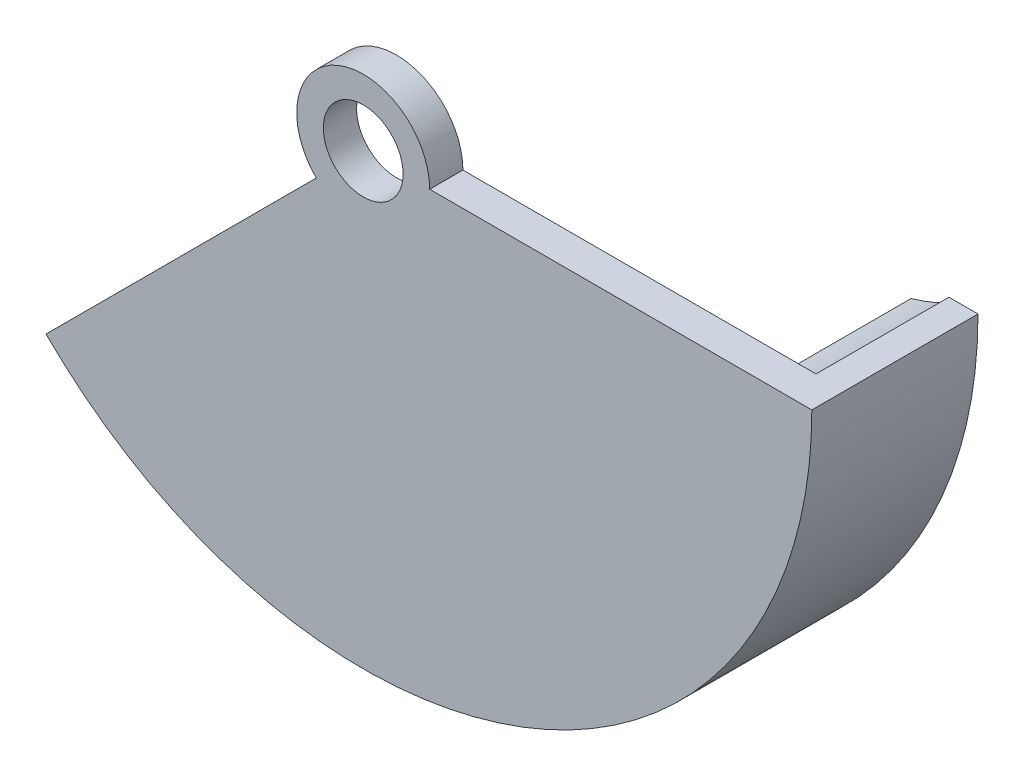
SolidWorks part; units mm, degrees
ref_plane "Front Plane" through (0, 0, 0) normal (0, 0, 1) x (1, 0, 0)
ref_plane "Top Plane" through (0, 0, 0) normal (0, 1, 0) x (1, 0, 0)
ref_plane "Right Plane" through (0, 0, 0) normal (1, 0, 0) x (0, 0, -1)
sketch "Sketch4" plane through (0, 0, 0) normal (0, 0, 1) x (1, 0, 0)
  arc A0 (11.9321, 56.2483) -> (10.5015, 56.5329) centre (0, 0) ccw construction
  arc A1 (10.5015, 56.5329) -> (8.9782, 62.4843) centre (-19.1705, 52.1088) ccw construction
  arc A2 (8.9782, 62.4843) -> (7.4999, 62.6789) centre (0, 0) ccw construction
  arc A3 (7.4999, 62.6789) -> (4.4881, 57.3246) centre (32.004, 45.3715) ccw construction
  arc A4 (11.9321, 56.2483) -> (10.5015, 56.5329) centre (0, 0) ccw
  arc A5 (10.5015, 56.5329) -> (8.9782, 62.4843) centre (-19.1705, 52.1088) ccw
  arc A6 (8.9782, 62.4843) -> (7.4999, 62.6789) centre (0, 0) ccw
  arc A7 (7.4999, 62.6789) -> (4.4881, 57.3246) centre (32.004, 45.3715) ccw
  arc A8 (15.6169, 61.1637) -> (11.9321, 56.2483) centre (37.6524, 40.806) ccw
  arc A9 (17.0572, 60.7778) -> (15.6169, 61.1637) centre (0, 0) ccw
  arc A10 (17.7907, 54.6785) -> (17.0572, 60.7778) centre (-12.2049, 54.1652) ccw
  arc A11 (19.1719, 54.2097) -> (17.7907, 54.6785) centre (0, 0) ccw
  arc A12 (23.4668, 58.6021) -> (19.1719, 54.2097) centre (42.6565, 35.5423) ccw
  arc A13 (24.8444, 58.0314) -> (23.4668, 58.6021) centre (0, 0) ccw
  arc A14 (24.7754, 51.8886) -> (24.8444, 58.0314) centre (-5.0305, 55.2949) ccw
  arc A15 (26.0837, 51.2435) -> (24.7754, 51.8886) centre (0, 0) ccw
  arc A16 (30.9151, 55.0377) -> (26.0837, 51.2435) centre (46.9308, 29.6704) ccw
  arc A17 (32.2065, 54.2921) -> (30.9151, 55.0377) centre (0, 0) ccw
  arc A18 (31.3363, 48.2108) -> (32.2065, 54.2921) centre (2.2299, 55.4785) ccw
  arc A19 (32.5491, 47.4005) -> (31.3363, 48.2108) centre (0, 0) ccw
  arc A20 (37.8345, 50.5316) -> (32.5491, 47.4005) centre (50.4021, 23.2909) ccw
  arc A21 (39.0175, 49.6239) -> (37.8345, 50.5316) centre (0, 0) ccw
  arc A22 (37.361, 43.7082) -> (39.0175, 49.6239) centre (9.4522, 54.7128) ccw
  arc A23 (38.4577, 42.7464) -> (37.361, 43.7082) centre (0, 0) ccw
  arc A24 (44.1065, 45.1609) -> (38.4577, 42.7464) centre (53.0109, 16.5128) ccw
  arc A25 (45.1609, 44.1065) -> (44.1065, 45.1609) centre (0, 0) ccw
  arc A26 (42.7464, 38.4577) -> (45.1609, 44.1065) centre (16.5128, 53.0109) ccw
  arc A27 (43.7082, 37.361) -> (42.7464, 38.4577) centre (0, 0) ccw
  arc A28 (49.6239, 39.0175) -> (43.7082, 37.361) centre (54.7128, 9.4522) ccw
  arc A29 (50.5316, 37.8345) -> (49.6239, 39.0175) centre (0, 0) ccw
  arc A30 (47.4005, 32.5491) -> (50.5316, 37.8345) centre (23.2909, 50.4021) ccw
  arc A31 (48.2108, 31.3363) -> (47.4005, 32.5491) centre (0, 0) ccw
  arc A32 (54.2921, 32.2065) -> (48.2108, 31.3363) centre (55.4785, 2.2299) ccw
  arc A33 (55.0377, 30.9151) -> (54.2921, 32.2065) centre (0, 0) ccw
  arc A34 (51.2435, 26.0837) -> (55.0377, 30.9151) centre (29.6704, 46.9308) ccw
  arc A35 (51.8886, 24.7754) -> (51.2435, 26.0837) centre (0, 0) ccw
  arc A36 (58.0314, 24.8444) -> (51.8886, 24.7754) centre (55.2949, -5.0305) ccw
  arc A37 (58.6021, 23.4668) -> (58.0314, 24.8444) centre (0, 0) ccw
  arc A38 (54.2097, 19.1719) -> (58.6021, 23.4668) centre (35.5423, 42.6565) ccw
  arc A39 (54.6785, 17.7907) -> (54.2097, 19.1719) centre (0, 0) ccw
  arc A40 (60.7778, 17.0572) -> (54.6785, 17.7907) centre (54.1652, -12.2049) ccw
  arc A41 (61.1637, 15.6169) -> (60.7778, 17.0572) centre (0, 0) ccw
  arc A42 (56.2483, 11.9321) -> (61.1637, 15.6169) centre (40.806, 37.6524) ccw
  arc A43 (56.5329, 10.5015) -> (56.2483, 11.9321) centre (0, 0) ccw
  arc A44 (62.4843, 8.9782) -> (56.5329, 10.5015) centre (52.1088, -19.1705) ccw
  arc A45 (62.6789, 7.4999) -> (62.4843, 8.9782) centre (0, 0) ccw
  arc A46 (57.3246, 4.4881) -> (62.6789, 7.4999) centre (45.3715, 32.004) ccw
  arc A47 (57.42, 3.0326) -> (57.3246, 4.4881) centre (0, 0) ccw
  arc A48 (63.1216, 0.7455) -> (57.42, 3.0326) centre (49.1607, -25.8081) ccw
  arc A49 (63.1216, -0.7455) -> (63.1216, 0.7455) centre (0, 0) ccw
  arc A50 (57.42, -3.0326) -> (63.1216, -0.7455) centre (49.1607, 25.8081) ccw
  arc A51 (57.3246, -4.4881) -> (57.42, -3.0326) centre (0, 0) ccw
  arc A52 (62.6789, -7.4999) -> (57.3246, -4.4881) centre (45.3715, -32.004) ccw
  arc A53 (62.4843, -8.9782) -> (62.6789, -7.4999) centre (0, 0) ccw
  arc A54 (56.5329, -10.5015) -> (62.4843, -8.9782) centre (52.1088, 19.1705) ccw
  arc A55 (56.2483, -11.9321) -> (56.5329, -10.5015) centre (0, 0) ccw
  arc A56 (61.1637, -15.6169) -> (56.2483, -11.9321) centre (40.806, -37.6524) ccw
  arc A57 (60.7778, -17.0572) -> (61.1637, -15.6169) centre (0, 0) ccw
  arc A58 (54.6785, -17.7907) -> (60.7778, -17.0572) centre (54.1652, 12.2049) ccw
  arc A59 (54.2097, -19.1719) -> (54.6785, -17.7907) centre (0, 0) ccw
  arc A60 (58.6021, -23.4668) -> (54.2097, -19.1719) centre (35.5423, -42.6565) ccw
  arc A61 (58.0314, -24.8444) -> (58.6021, -23.4668) centre (0, 0) ccw
  arc A62 (51.8886, -24.7754) -> (58.0314, -24.8444) centre (55.2949, 5.0305) ccw
  arc A63 (51.2435, -26.0837) -> (51.8886, -24.7754) centre (0, 0) ccw
  arc A64 (55.0377, -30.9151) -> (51.2435, -26.0837) centre (29.6704, -46.9308) ccw
  arc A65 (54.2921, -32.2065) -> (55.0377, -30.9151) centre (0, 0) ccw
  arc A66 (48.2108, -31.3363) -> (54.2921, -32.2065) centre (55.4785, -2.2299) ccw
  arc A67 (47.4005, -32.5491) -> (48.2108, -31.3363) centre (0, 0) ccw
  arc A68 (50.5316, -37.8345) -> (47.4005, -32.5491) centre (23.2909, -50.4021) ccw
  arc A69 (49.6239, -39.0175) -> (50.5316, -37.8345) centre (0, 0) ccw
  arc A70 (43.7082, -37.361) -> (49.6239, -39.0175) centre (54.7128, -9.4522) ccw
  arc A71 (42.7464, -38.4577) -> (43.7082, -37.361) centre (0, 0) ccw
  arc A72 (45.1609, -44.1065) -> (42.7464, -38.4577) centre (16.5128, -53.0109) ccw
  arc A73 (44.1065, -45.1609) -> (45.1609, -44.1065) centre (0, 0) ccw
  arc A74 (38.4577, -42.7464) -> (44.1065, -45.1609) centre (53.0109, -16.5128) ccw
  arc A75 (37.361, -43.7082) -> (38.4577, -42.7464) centre (0, 0) ccw
  arc A76 (39.0175, -49.6239) -> (37.361, -43.7082) centre (9.4522, -54.7128) ccw
  arc A77 (37.8345, -50.5316) -> (39.0175, -49.6239) centre (0, 0) ccw
  arc A78 (32.5491, -47.4005) -> (37.8345, -50.5316) centre (50.4021, -23.2909) ccw
  arc A79 (31.3363, -48.2108) -> (32.5491, -47.4005) centre (0, 0) ccw
  arc A80 (32.2065, -54.2921) -> (31.3363, -48.2108) centre (2.2299, -55.4785) ccw
  arc A81 (30.9151, -55.0377) -> (32.2065, -54.2921) centre (0, 0) ccw
  arc A82 (26.0837, -51.2435) -> (30.9151, -55.0377) centre (46.9308, -29.6704) ccw
  arc A83 (24.7754, -51.8886) -> (26.0837, -51.2435) centre (0, 0) ccw
  arc A84 (24.8444, -58.0314) -> (24.7754, -51.8886) centre (-5.0305, -55.2949) ccw
  arc A85 (23.4668, -58.6021) -> (24.8444, -58.0314) centre (0, 0) ccw
  arc A86 (19.1719, -54.2097) -> (23.4668, -58.6021) centre (42.6565, -35.5423) ccw
  arc A87 (17.7907, -54.6785) -> (19.1719, -54.2097) centre (0, 0) ccw
  arc A88 (17.0572, -60.7778) -> (17.7907, -54.6785) centre (-12.2049, -54.1652) ccw
  arc A89 (15.6169, -61.1637) -> (17.0572, -60.7778) centre (0, 0) ccw
  arc A90 (11.9321, -56.2483) -> (15.6169, -61.1637) centre (37.6524, -40.806) ccw
  arc A91 (10.5015, -56.5329) -> (11.9321, -56.2483) centre (0, 0) ccw
  arc A92 (8.9782, -62.4843) -> (10.5015, -56.5329) centre (-19.1705, -52.1088) ccw
  arc A93 (7.4999, -62.6789) -> (8.9782, -62.4843) centre (0, 0) ccw
  arc A94 (4.4881, -57.3246) -> (7.4999, -62.6789) centre (32.004, -45.3715) ccw
  arc A95 (3.0326, -57.42) -> (4.4881, -57.3246) centre (0, 0) ccw
  arc A96 (0.7455, -63.1216) -> (3.0326, -57.42) centre (-25.8081, -49.1607) ccw
  arc A97 (-0.7455, -63.1216) -> (0.7455, -63.1216) centre (0, 0) ccw
  arc A98 (-3.0326, -57.42) -> (-0.7455, -63.1216) centre (25.8081, -49.1607) ccw
  arc A99 (-4.4881, -57.3246) -> (-3.0326, -57.42) centre (0, 0) ccw
  arc A100 (-7.4999, -62.6789) -> (-4.4881, -57.3246) centre (-32.004, -45.3715) ccw
  arc A101 (-8.9782, -62.4843) -> (-7.4999, -62.6789) centre (0, 0) ccw
  arc A102 (-10.5015, -56.5329) -> (-8.9782, -62.4843) centre (19.1705, -52.1088) ccw
  arc A103 (-11.9321, -56.2483) -> (-10.5015, -56.5329) centre (0, 0) ccw
  arc A104 (-15.6169, -61.1637) -> (-11.9321, -56.2483) centre (-37.6524, -40.806) ccw
  arc A105 (-17.0572, -60.7778) -> (-15.6169, -61.1637) centre (0, 0) ccw
  arc A106 (-17.7907, -54.6785) -> (-17.0572, -60.7778) centre (12.2049, -54.1652) ccw
  arc A107 (-19.1719, -54.2097) -> (-17.7907, -54.6785) centre (0, 0) ccw
  arc A108 (-23.4668, -58.6021) -> (-19.1719, -54.2097) centre (-42.6565, -35.5423) ccw
  arc A109 (-24.8444, -58.0314) -> (-23.4668, -58.6021) centre (0, 0) ccw
  arc A110 (-24.7754, -51.8886) -> (-24.8444, -58.0314) centre (5.0305, -55.2949) ccw
  arc A111 (-26.0837, -51.2435) -> (-24.7754, -51.8886) centre (0, 0) ccw
  arc A112 (-30.9151, -55.0377) -> (-26.0837, -51.2435) centre (-46.9308, -29.6704) ccw
  arc A113 (-32.2065, -54.2921) -> (-30.9151, -55.0377) centre (0, 0) ccw
  arc A114 (-31.3363, -48.2108) -> (-32.2065, -54.2921) centre (-2.2299, -55.4785) ccw
  arc A115 (-32.5491, -47.4005) -> (-31.3363, -48.2108) centre (0, 0) ccw
  arc A116 (-37.8345, -50.5316) -> (-32.5491, -47.4005) centre (-50.4021, -23.2909) ccw
  arc A117 (-39.0175, -49.6239) -> (-37.8345, -50.5316) centre (0, 0) ccw
  arc A118 (-37.361, -43.7082) -> (-39.0175, -49.6239) centre (-9.4522, -54.7128) ccw
  arc A119 (-38.4577, -42.7464) -> (-37.361, -43.7082) centre (0, 0) ccw
  arc A120 (-44.1065, -45.1609) -> (-38.4577, -42.7464) centre (-53.0109, -16.5128) ccw
  arc A121 (-45.1609, -44.1065) -> (-44.1065, -45.1609) centre (0, 0) ccw
  arc A122 (-42.7464, -38.4577) -> (-45.1609, -44.1065) centre (-16.5128, -53.0109) ccw
  arc A123 (-43.7082, -37.361) -> (-42.7464, -38.4577) centre (0, 0) ccw
  arc A124 (-49.6239, -39.0175) -> (-43.7082, -37.361) centre (-54.7128, -9.4522) ccw
  arc A125 (-50.5316, -37.8345) -> (-49.6239, -39.0175) centre (0, 0) ccw
  arc A126 (-47.4005, -32.5491) -> (-50.5316, -37.8345) centre (-23.2909, -50.4021) ccw
  arc A127 (-48.2108, -31.3363) -> (-47.4005, -32.5491) centre (0, 0) ccw
  arc A128 (-54.2921, -32.2065) -> (-48.2108, -31.3363) centre (-55.4785, -2.2299) ccw
  arc A129 (-55.0377, -30.9151) -> (-54.2921, -32.2065) centre (0, 0) ccw
  arc A130 (-51.2435, -26.0837) -> (-55.0377, -30.9151) centre (-29.6704, -46.9308) ccw
  arc A131 (-51.8886, -24.7754) -> (-51.2435, -26.0837) centre (0, 0) ccw
  arc A132 (-58.0314, -24.8444) -> (-51.8886, -24.7754) centre (-55.2949, 5.0305) ccw
  arc A133 (-58.6021, -23.4668) -> (-58.0314, -24.8444) centre (0, 0) ccw
  arc A134 (-54.2097, -19.1719) -> (-58.6021, -23.4668) centre (-35.5423, -42.6565) ccw
  arc A135 (-54.6785, -17.7907) -> (-54.2097, -19.1719) centre (0, 0) ccw
  arc A136 (-60.7778, -17.0572) -> (-54.6785, -17.7907) centre (-54.1652, 12.2049) ccw
  arc A137 (-61.1637, -15.6169) -> (-60.7778, -17.0572) centre (0, 0) ccw
  arc A138 (-56.2483, -11.9321) -> (-61.1637, -15.6169) centre (-40.806, -37.6524) ccw
  arc A139 (-56.5329, -10.5015) -> (-56.2483, -11.9321) centre (0, 0) ccw
  arc A140 (-62.4843, -8.9782) -> (-56.5329, -10.5015) centre (-52.1088, 19.1705) ccw
  arc A141 (-62.6789, -7.4999) -> (-62.4843, -8.9782) centre (0, 0) ccw
  arc A142 (-57.3246, -4.4881) -> (-62.6789, -7.4999) centre (-45.3715, -32.004) ccw
  arc A143 (-57.42, -3.0326) -> (-57.3246, -4.4881) centre (0, 0) ccw
  arc A144 (-63.1216, -0.7455) -> (-57.42, -3.0326) centre (-49.1607, 25.8081) ccw
  arc A145 (-63.1216, 0.7455) -> (-63.1216, -0.7455) centre (0, 0) ccw
  arc A146 (-57.42, 3.0326) -> (-63.1216, 0.7455) centre (-49.1607, -25.8081) ccw
  arc A147 (-57.3246, 4.4881) -> (-57.42, 3.0326) centre (0, 0) ccw
  arc A148 (-62.6789, 7.4999) -> (-57.3246, 4.4881) centre (-45.3715, 32.004) ccw
  arc A149 (-62.4843, 8.9782) -> (-62.6789, 7.4999) centre (0, 0) ccw
  arc A150 (-56.5329, 10.5015) -> (-62.4843, 8.9782) centre (-52.1088, -19.1705) ccw
  arc A151 (-56.2483, 11.9321) -> (-56.5329, 10.5015) centre (0, 0) ccw
  arc A152 (-61.1637, 15.6169) -> (-56.2483, 11.9321) centre (-40.806, 37.6524) ccw
  arc A153 (-60.7778, 17.0572) -> (-61.1637, 15.6169) centre (0, 0) ccw
  arc A154 (-54.6785, 17.7907) -> (-60.7778, 17.0572) centre (-54.1652, -12.2049) ccw
  arc A155 (-54.2097, 19.1719) -> (-54.6785, 17.7907) centre (0, 0) ccw
  arc A156 (-58.6021, 23.4668) -> (-54.2097, 19.1719) centre (-35.5423, 42.6565) ccw
  arc A157 (-58.0314, 24.8444) -> (-58.6021, 23.4668) centre (0, 0) ccw
  arc A158 (-51.8886, 24.7754) -> (-58.0314, 24.8444) centre (-55.2949, -5.0305) ccw
  arc A159 (-51.2435, 26.0837) -> (-51.8886, 24.7754) centre (0, 0) ccw
  arc A160 (-55.0377, 30.9151) -> (-51.2435, 26.0837) centre (-29.6704, 46.9308) ccw
  arc A161 (-54.2921, 32.2065) -> (-55.0377, 30.9151) centre (0, 0) ccw
  arc A162 (-48.2108, 31.3363) -> (-54.2921, 32.2065) centre (-55.4785, 2.2299) ccw
  arc A163 (-47.4005, 32.5491) -> (-48.2108, 31.3363) centre (0, 0) ccw
  arc A164 (-50.5316, 37.8345) -> (-47.4005, 32.5491) centre (-23.2909, 50.4021) ccw
  arc A165 (-49.6239, 39.0175) -> (-50.5316, 37.8345) centre (0, 0) ccw
  arc A166 (-43.7082, 37.361) -> (-49.6239, 39.0175) centre (-54.7128, 9.4522) ccw
  arc A167 (-42.7464, 38.4577) -> (-43.7082, 37.361) centre (0, 0) ccw
  arc A168 (-45.1609, 44.1065) -> (-42.7464, 38.4577) centre (-16.5128, 53.0109) ccw
  arc A169 (-44.1065, 45.1609) -> (-45.1609, 44.1065) centre (0, 0) ccw
  arc A170 (-38.4577, 42.7464) -> (-44.1065, 45.1609) centre (-53.0109, 16.5128) ccw
  arc A171 (-37.361, 43.7082) -> (-38.4577, 42.7464) centre (0, 0) ccw
  arc A172 (-39.0175, 49.6239) -> (-37.361, 43.7082) centre (-9.4522, 54.7128) ccw
  arc A173 (-37.8345, 50.5316) -> (-39.0175, 49.6239) centre (0, 0) ccw
  arc A174 (-32.5491, 47.4005) -> (-37.8345, 50.5316) centre (-50.4021, 23.2909) ccw
  arc A175 (-31.3363, 48.2108) -> (-32.5491, 47.4005) centre (0, 0) ccw
  arc A176 (-32.2065, 54.2921) -> (-31.3363, 48.2108) centre (-2.2299, 55.4785) ccw
  arc A177 (-30.9151, 55.0377) -> (-32.2065, 54.2921) centre (0, 0) ccw
  arc A178 (-26.0837, 51.2435) -> (-30.9151, 55.0377) centre (-46.9308, 29.6704) ccw
  arc A179 (-24.7754, 51.8886) -> (-26.0837, 51.2435) centre (0, 0) ccw
  arc A180 (-24.8444, 58.0314) -> (-24.7754, 51.8886) centre (5.0305, 55.2949) ccw
  arc A181 (-23.4668, 58.6021) -> (-24.8444, 58.0314) centre (0, 0) ccw
  arc A182 (-19.1719, 54.2097) -> (-23.4668, 58.6021) centre (-42.6565, 35.5423) ccw
  arc A183 (-17.7907, 54.6785) -> (-19.1719, 54.2097) centre (0, 0) ccw
  arc A184 (-17.0572, 60.7778) -> (-17.7907, 54.6785) centre (12.2049, 54.1652) ccw
  arc A185 (-15.6169, 61.1637) -> (-17.0572, 60.7778) centre (0, 0) ccw
  arc A186 (-11.9321, 56.2483) -> (-15.6169, 61.1637) centre (-37.6524, 40.806) ccw
  arc A187 (-10.5015, 56.5329) -> (-11.9321, 56.2483) centre (0, 0) ccw
  arc A188 (-8.9782, 62.4843) -> (-10.5015, 56.5329) centre (19.1705, 52.1088) ccw
  arc A189 (-7.4999, 62.6789) -> (-8.9782, 62.4843) centre (0, 0) ccw
  arc A190 (-4.4881, 57.3246) -> (-7.4999, 62.6789) centre (-32.004, 45.3715) ccw
  arc A191 (-3.0326, 57.42) -> (-4.4881, 57.3246) centre (0, 0) ccw
  arc A192 (-0.7455, 63.1216) -> (-3.0326, 57.42) centre (25.8081, 49.1607) ccw
  arc A193 (0.7455, 63.1216) -> (-0.7455, 63.1216) centre (0, 0) ccw
  arc A194 (3.0326, 57.42) -> (0.7455, 63.1216) centre (-25.8081, 49.1607) ccw
  arc A195 (4.4881, 57.3246) -> (3.0326, 57.42) centre (0, 0) ccw
  circle A196 centre (0, 0) radius 67.5
  dimension "D1" = 48
extrude "Boss-Extrude1" add sketch "Sketch4" along normal blind 50
sketch "Sketch5" plane through (0, 0, 0) normal (0, 0, -1) x (-1, 0, 0)
  line L0 (0, 0) -> (-67.5, 0)
  line L1 (0, 0) -> (47.7297, -47.7297)
  circle A0 centre (0, 0) radius 67.5 construction
  arc A1 (47.7297, -47.7297) -> (-67.5, 0) centre (0, 0) ccw
extrude "Cut-Extrude2" cut sketch "Sketch5" against normal blind 250 contours L1 A1 L0
sketch "Sketch6" plane through (0, 0, 50) normal (0, 0, 1) x (1, 0, 0)
  line L0 (0, 0) -> (67.5, 0)
  line L1 (0, 0) -> (-47.7297, -47.7297)
  arc A0 (67.5, 0) -> (-47.7297, -47.7297) centre (0, 0) cw
  arc A1 (-47.7297, -47.7297) -> (67.5, 0) centre (0, 0) ccw construction
extrude "Boss-Extrude2" add sketch "Sketch6" along normal blind 5 contours A0 L0 L1
sketch "Sketch7" plane through (0, 0, 55) normal (0, 0, 1) x (1, 0, 0)
  circle A0 centre (0, 0) radius 6
extrude "Cut-Extrude3" cut sketch "Sketch7" against normal blind 5
sketch "Sketch8" plane through (0, 0, 55) normal (0, 0, 1) x (1, 0, 0)
  circle A0 centre (0, 0) radius 6
  circle A1 centre (0, 0) radius 10
extrude "Boss-Extrude3" add sketch "Sketch8" against normal blind 5
sketch "Sketch9" plane through (0, 0, 0) normal (0, 0, -1) x (-1, 0, 0)
  line L2 (47.7297, -47.7297) -> (44.6368, -44.6368)
  line L3 (-63.126, 0) -> (-67.5, 0)
  line L4 (47.7297, -47.7297) -> (44.6368, -44.6368)
  line L5 (-63.126, 0) -> (-67.5, 0)
  arc A74 (-67.5, 0) -> (47.7297, -47.7297) centre (0, 0) ccw
  arc A75 (44.1065, -45.1609) -> (44.6368, -44.6368) centre (0, 0) ccw
  arc A76 (38.4577, -42.7464) -> (44.1065, -45.1609) centre (53.0109, -16.5128) ccw
  arc A77 (37.361, -43.7082) -> (38.4577, -42.7464) centre (0, 0) ccw
  arc A78 (39.0175, -49.6239) -> (37.361, -43.7082) centre (9.4522, -54.7128) ccw
  arc A79 (37.8345, -50.5316) -> (39.0175, -49.6239) centre (0, 0) ccw
  arc A80 (32.5491, -47.4005) -> (37.8345, -50.5316) centre (50.4021, -23.2909) ccw
  arc A81 (31.3363, -48.2108) -> (32.5491, -47.4005) centre (0, 0) ccw
  arc A82 (32.2065, -54.2921) -> (31.3363, -48.2108) centre (2.2299, -55.4785) ccw
  arc A83 (30.9151, -55.0377) -> (32.2065, -54.2921) centre (0, 0) ccw
  arc A84 (26.0837, -51.2435) -> (30.9151, -55.0377) centre (46.9308, -29.6704) ccw
  arc A85 (24.7754, -51.8886) -> (26.0837, -51.2435) centre (0, 0) ccw
  arc A86 (24.8444, -58.0314) -> (24.7754, -51.8886) centre (-5.0305, -55.2949) ccw
  arc A87 (23.4668, -58.6021) -> (24.8444, -58.0314) centre (0, 0) ccw
  arc A88 (19.1719, -54.2097) -> (23.4668, -58.6021) centre (42.6565, -35.5423) ccw
  arc A89 (17.7907, -54.6785) -> (19.1719, -54.2097) centre (0, 0) ccw
  arc A90 (17.0572, -60.7778) -> (17.7907, -54.6785) centre (-12.2049, -54.1652) ccw
  arc A91 (15.6169, -61.1637) -> (17.0572, -60.7778) centre (0, 0) ccw
  arc A92 (11.9321, -56.2483) -> (15.6169, -61.1637) centre (37.6524, -40.806) ccw
  arc A93 (10.5015, -56.5329) -> (11.9321, -56.2483) centre (0, 0) ccw
  arc A94 (8.9782, -62.4843) -> (10.5015, -56.5329) centre (-19.1705, -52.1088) ccw
  arc A95 (7.4999, -62.6789) -> (8.9782, -62.4843) centre (0, 0) ccw
  arc A96 (4.4881, -57.3246) -> (7.4999, -62.6789) centre (32.004, -45.3715) ccw
  arc A97 (3.0326, -57.42) -> (4.4881, -57.3246) centre (0, 0) ccw
  arc A98 (0.7455, -63.1216) -> (3.0326, -57.42) centre (-25.8081, -49.1607) ccw
  arc A99 (-0.7455, -63.1216) -> (0.7455, -63.1216) centre (0, 0) ccw
  arc A100 (-3.0326, -57.42) -> (-0.7455, -63.1216) centre (25.8081, -49.1607) ccw
  arc A101 (-4.4881, -57.3246) -> (-3.0326, -57.42) centre (0, 0) ccw
  arc A102 (-7.4999, -62.6789) -> (-4.4881, -57.3246) centre (-32.004, -45.3715) ccw
  arc A103 (-8.9782, -62.4843) -> (-7.4999, -62.6789) centre (0, 0) ccw
  arc A104 (-10.5015, -56.5329) -> (-8.9782, -62.4843) centre (19.1705, -52.1088) ccw
  arc A105 (-11.9321, -56.2483) -> (-10.5015, -56.5329) centre (0, 0) ccw
  arc A106 (-15.6169, -61.1637) -> (-11.9321, -56.2483) centre (-37.6524, -40.806) ccw
  arc A107 (-17.0572, -60.7778) -> (-15.6169, -61.1637) centre (0, 0) ccw
  arc A108 (-17.7907, -54.6785) -> (-17.0572, -60.7778) centre (12.2049, -54.1652) ccw
  arc A109 (-19.1719, -54.2097) -> (-17.7907, -54.6785) centre (0, 0) ccw
  arc A110 (-23.4668, -58.6021) -> (-19.1719, -54.2097) centre (-42.6565, -35.5423) ccw
  arc A111 (-24.8444, -58.0314) -> (-23.4668, -58.6021) centre (0, 0) ccw
  arc A112 (-24.7754, -51.8886) -> (-24.8444, -58.0314) centre (5.0305, -55.2949) ccw
  arc A113 (-26.0837, -51.2435) -> (-24.7754, -51.8886) centre (0, 0) ccw
  arc A114 (-30.9151, -55.0377) -> (-26.0837, -51.2435) centre (-46.9308, -29.6704) ccw
  arc A115 (-32.2065, -54.2921) -> (-30.9151, -55.0377) centre (0, 0) ccw
  arc A116 (-31.3363, -48.2108) -> (-32.2065, -54.2921) centre (-2.2299, -55.4785) ccw
  arc A117 (-32.5491, -47.4005) -> (-31.3363, -48.2108) centre (0, 0) ccw
  arc A118 (-37.8345, -50.5316) -> (-32.5491, -47.4005) centre (-50.4021, -23.2909) ccw
  arc A119 (-39.0175, -49.6239) -> (-37.8345, -50.5316) centre (0, 0) ccw
  arc A120 (-37.361, -43.7082) -> (-39.0175, -49.6239) centre (-9.4522, -54.7128) ccw
  arc A121 (-38.4577, -42.7464) -> (-37.361, -43.7082) centre (0, 0) ccw
  arc A122 (-44.1065, -45.1609) -> (-38.4577, -42.7464) centre (-53.0109, -16.5128) ccw
  arc A123 (-45.1609, -44.1065) -> (-44.1065, -45.1609) centre (0, 0) ccw
  arc A124 (-42.7464, -38.4577) -> (-45.1609, -44.1065) centre (-16.5128, -53.0109) ccw
  arc A125 (-43.7082, -37.361) -> (-42.7464, -38.4577) centre (0, 0) ccw
  arc A126 (-49.6239, -39.0175) -> (-43.7082, -37.361) centre (-54.7128, -9.4522) ccw
  arc A127 (-50.5316, -37.8345) -> (-49.6239, -39.0175) centre (0, 0) ccw
  arc A128 (-47.4005, -32.5491) -> (-50.5316, -37.8345) centre (-23.2909, -50.4021) ccw
  arc A129 (-48.2108, -31.3363) -> (-47.4005, -32.5491) centre (0, 0) ccw
  arc A130 (-54.2921, -32.2065) -> (-48.2108, -31.3363) centre (-55.4785, -2.2299) ccw
  arc A131 (-55.0377, -30.9151) -> (-54.2921, -32.2065) centre (0, 0) ccw
  arc A132 (-51.2435, -26.0837) -> (-55.0377, -30.9151) centre (-29.6704, -46.9308) ccw
  arc A133 (-51.8886, -24.7754) -> (-51.2435, -26.0837) centre (0, 0) ccw
  arc A134 (-58.0314, -24.8444) -> (-51.8886, -24.7754) centre (-55.2949, 5.0305) ccw
  arc A135 (-58.6021, -23.4668) -> (-58.0314, -24.8444) centre (0, 0) ccw
  arc A136 (-54.2097, -19.1719) -> (-58.6021, -23.4668) centre (-35.5423, -42.6565) ccw
  arc A137 (-54.6785, -17.7907) -> (-54.2097, -19.1719) centre (0, 0) ccw
  arc A138 (-60.7778, -17.0572) -> (-54.6785, -17.7907) centre (-54.1652, 12.2049) ccw
  arc A139 (-61.1637, -15.6169) -> (-60.7778, -17.0572) centre (0, 0) ccw
  arc A140 (-56.2483, -11.9321) -> (-61.1637, -15.6169) centre (-40.806, -37.6524) ccw
  arc A141 (-56.5329, -10.5015) -> (-56.2483, -11.9321) centre (0, 0) ccw
  arc A142 (-62.4843, -8.9782) -> (-56.5329, -10.5015) centre (-52.1088, 19.1705) ccw
  arc A143 (-62.6789, -7.4999) -> (-62.4843, -8.9782) centre (0, 0) ccw
  arc A144 (-57.3246, -4.4881) -> (-62.6789, -7.4999) centre (-45.3715, -32.004) ccw
  arc A145 (-57.42, -3.0326) -> (-57.3246, -4.4881) centre (0, 0) ccw
  arc A146 (-63.1216, -0.7455) -> (-57.42, -3.0326) centre (-49.1607, 25.8081) ccw
  arc A147 (-63.126, 0) -> (-63.1216, -0.7455) centre (0, 0) ccw
  arc A148 (-67.5, 0) -> (47.7297, -47.7297) centre (0, 0) ccw
  arc A149 (44.1065, -45.1609) -> (44.6368, -44.6368) centre (0, 0) ccw
  arc A150 (38.4577, -42.7464) -> (44.1065, -45.1609) centre (53.0109, -16.5128) ccw
  arc A151 (37.361, -43.7082) -> (38.4577, -42.7464) centre (0, 0) ccw
  arc A152 (39.0175, -49.6239) -> (37.361, -43.7082) centre (9.4522, -54.7128) ccw
  arc A153 (37.8345, -50.5316) -> (39.0175, -49.6239) centre (0, 0) ccw
  arc A154 (32.5491, -47.4005) -> (37.8345, -50.5316) centre (50.4021, -23.2909) ccw
  arc A155 (31.3363, -48.2108) -> (32.5491, -47.4005) centre (0, 0) ccw
  arc A156 (32.2065, -54.2921) -> (31.3363, -48.2108) centre (2.2299, -55.4785) ccw
  arc A157 (30.9151, -55.0377) -> (32.2065, -54.2921) centre (0, 0) ccw
  arc A158 (26.0837, -51.2435) -> (30.9151, -55.0377) centre (46.9308, -29.6704) ccw
  arc A159 (24.7754, -51.8886) -> (26.0837, -51.2435) centre (0, 0) ccw
  arc A160 (24.8444, -58.0314) -> (24.7754, -51.8886) centre (-5.0305, -55.2949) ccw
  arc A161 (23.4668, -58.6021) -> (24.8444, -58.0314) centre (0, 0) ccw
  arc A162 (19.1719, -54.2097) -> (23.4668, -58.6021) centre (42.6565, -35.5423) ccw
  arc A163 (17.7907, -54.6785) -> (19.1719, -54.2097) centre (0, 0) ccw
  arc A164 (17.0572, -60.7778) -> (17.7907, -54.6785) centre (-12.2049, -54.1652) ccw
  arc A165 (15.6169, -61.1637) -> (17.0572, -60.7778) centre (0, 0) ccw
  arc A166 (11.9321, -56.2483) -> (15.6169, -61.1637) centre (37.6524, -40.806) ccw
  arc A167 (10.5015, -56.5329) -> (11.9321, -56.2483) centre (0, 0) ccw
  arc A168 (8.9782, -62.4843) -> (10.5015, -56.5329) centre (-19.1705, -52.1088) ccw
  arc A169 (7.4999, -62.6789) -> (8.9782, -62.4843) centre (0, 0) ccw
  arc A170 (4.4881, -57.3246) -> (7.4999, -62.6789) centre (32.004, -45.3715) ccw
  arc A171 (3.0326, -57.42) -> (4.4881, -57.3246) centre (0, 0) ccw
  arc A172 (0.7455, -63.1216) -> (3.0326, -57.42) centre (-25.8081, -49.1607) ccw
  arc A173 (-0.7455, -63.1216) -> (0.7455, -63.1216) centre (0, 0) ccw
  arc A174 (-3.0326, -57.42) -> (-0.7455, -63.1216) centre (25.8081, -49.1607) ccw
  arc A175 (-4.4881, -57.3246) -> (-3.0326, -57.42) centre (0, 0) ccw
  arc A176 (-7.4999, -62.6789) -> (-4.4881, -57.3246) centre (-32.004, -45.3715) ccw
  arc A177 (-8.9782, -62.4843) -> (-7.4999, -62.6789) centre (0, 0) ccw
  arc A178 (-10.5015, -56.5329) -> (-8.9782, -62.4843) centre (19.1705, -52.1088) ccw
  arc A179 (-11.9321, -56.2483) -> (-10.5015, -56.5329) centre (0, 0) ccw
  arc A180 (-15.6169, -61.1637) -> (-11.9321, -56.2483) centre (-37.6524, -40.806) ccw
  arc A181 (-17.0572, -60.7778) -> (-15.6169, -61.1637) centre (0, 0) ccw
  arc A182 (-17.7907, -54.6785) -> (-17.0572, -60.7778) centre (12.2049, -54.1652) ccw
  arc A183 (-19.1719, -54.2097) -> (-17.7907, -54.6785) centre (0, 0) ccw
  arc A184 (-23.4668, -58.6021) -> (-19.1719, -54.2097) centre (-42.6565, -35.5423) ccw
  arc A185 (-24.8444, -58.0314) -> (-23.4668, -58.6021) centre (0, 0) ccw
  arc A186 (-24.7754, -51.8886) -> (-24.8444, -58.0314) centre (5.0305, -55.2949) ccw
  arc A187 (-26.0837, -51.2435) -> (-24.7754, -51.8886) centre (0, 0) ccw
  arc A188 (-30.9151, -55.0377) -> (-26.0837, -51.2435) centre (-46.9308, -29.6704) ccw
  arc A189 (-32.2065, -54.2921) -> (-30.9151, -55.0377) centre (0, 0) ccw
  arc A190 (-31.3363, -48.2108) -> (-32.2065, -54.2921) centre (-2.2299, -55.4785) ccw
  arc A191 (-32.5491, -47.4005) -> (-31.3363, -48.2108) centre (0, 0) ccw
  arc A192 (-37.8345, -50.5316) -> (-32.5491, -47.4005) centre (-50.4021, -23.2909) ccw
  arc A193 (-39.0175, -49.6239) -> (-37.8345, -50.5316) centre (0, 0) ccw
  arc A194 (-37.361, -43.7082) -> (-39.0175, -49.6239) centre (-9.4522, -54.7128) ccw
  arc A195 (-38.4577, -42.7464) -> (-37.361, -43.7082) centre (0, 0) ccw
  arc A196 (-44.1065, -45.1609) -> (-38.4577, -42.7464) centre (-53.0109, -16.5128) ccw
  arc A197 (-45.1609, -44.1065) -> (-44.1065, -45.1609) centre (0, 0) ccw
  arc A198 (-42.7464, -38.4577) -> (-45.1609, -44.1065) centre (-16.5128, -53.0109) ccw
  arc A199 (-43.7082, -37.361) -> (-42.7464, -38.4577) centre (0, 0) ccw
  arc A200 (-49.6239, -39.0175) -> (-43.7082, -37.361) centre (-54.7128, -9.4522) ccw
  arc A201 (-50.5316, -37.8345) -> (-49.6239, -39.0175) centre (0, 0) ccw
  arc A202 (-47.4005, -32.5491) -> (-50.5316, -37.8345) centre (-23.2909, -50.4021) ccw
  arc A203 (-48.2108, -31.3363) -> (-47.4005, -32.5491) centre (0, 0) ccw
  arc A204 (-54.2921, -32.2065) -> (-48.2108, -31.3363) centre (-55.4785, -2.2299) ccw
  arc A205 (-55.0377, -30.9151) -> (-54.2921, -32.2065) centre (0, 0) ccw
  arc A206 (-51.2435, -26.0837) -> (-55.0377, -30.9151) centre (-29.6704, -46.9308) ccw
  arc A207 (-51.8886, -24.7754) -> (-51.2435, -26.0837) centre (0, 0) ccw
  arc A208 (-58.0314, -24.8444) -> (-51.8886, -24.7754) centre (-55.2949, 5.0305) ccw
  arc A209 (-58.6021, -23.4668) -> (-58.0314, -24.8444) centre (0, 0) ccw
  arc A210 (-54.2097, -19.1719) -> (-58.6021, -23.4668) centre (-35.5423, -42.6565) ccw
  arc A211 (-54.6785, -17.7907) -> (-54.2097, -19.1719) centre (0, 0) ccw
  arc A212 (-60.7778, -17.0572) -> (-54.6785, -17.7907) centre (-54.1652, 12.2049) ccw
  arc A213 (-61.1637, -15.6169) -> (-60.7778, -17.0572) centre (0, 0) ccw
  arc A214 (-56.2483, -11.9321) -> (-61.1637, -15.6169) centre (-40.806, -37.6524) ccw
  arc A215 (-56.5329, -10.5015) -> (-56.2483, -11.9321) centre (0, 0) ccw
  arc A216 (-62.4843, -8.9782) -> (-56.5329, -10.5015) centre (-52.1088, 19.1705) ccw
  arc A217 (-62.6789, -7.4999) -> (-62.4843, -8.9782) centre (0, 0) ccw
  arc A218 (-57.3246, -4.4881) -> (-62.6789, -7.4999) centre (-45.3715, -32.004) ccw
  arc A219 (-57.42, -3.0326) -> (-57.3246, -4.4881) centre (0, 0) ccw
  arc A220 (-63.1216, -0.7455) -> (-57.42, -3.0326) centre (-49.1607, 25.8081) ccw
  arc A221 (-63.126, 0) -> (-63.1216, -0.7455) centre (0, 0) ccw
  dimension "D1" = 0
extrude "Cut-Extrude5" cut sketch "Sketch9" against normal blind 30
